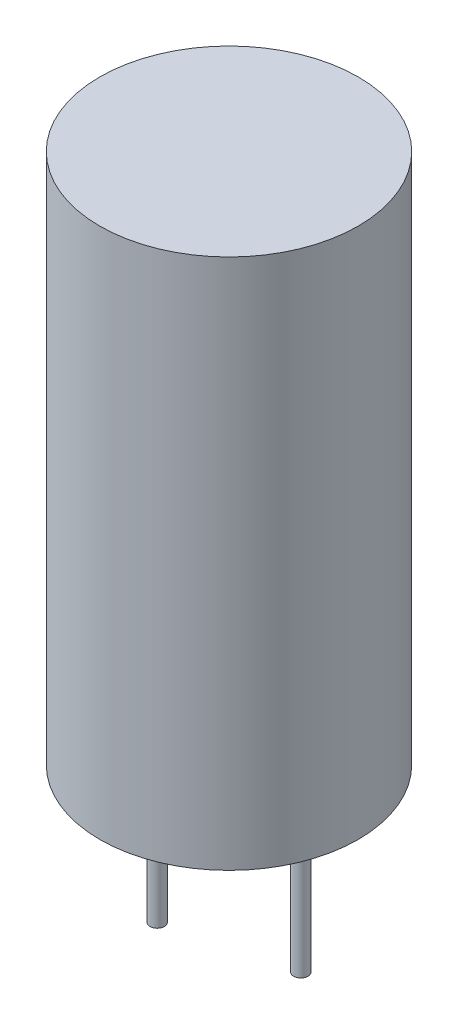
SolidWorks part; units mm, degrees
ref_plane "前视基准面" through (0, 0, 0) normal (0, 0, 1) x (1, 0, 0)
ref_plane "上视基准面" through (0, 0, 0) normal (0, 1, 0) x (1, 0, 0)
ref_plane "右视基准面" through (0, 0, 0) normal (1, 0, 0) x (0, 0, -1)
sketch "草图1" plane through (0, 0, 0) normal (0, 1, 0) x (1, 0, 0)
  circle A0 centre (0, 0) radius 9
  dimension "D1" = 18
extrude "拉伸1" add sketch "草图1" along normal blind 37
sketch "草图2" plane through (0, 0, 0) normal (0, -1, 0) x (1, 0, 0)
  line L0 (4.8023, 0) -> (-11.2367, 0) construction
  circle A0 centre (-5, 0) radius 0.5
  dimension "D2" = 1
  dimension "D1" = 5
extrude "拉伸2" add sketch "草图2" along normal blind 12
sketch "草图3" plane through (0, 0, 0) normal (0, -1, 0) x (1, 0, 0)
  line L0 (7.1249, 0) -> (-2.8562, 0) construction
  circle A0 centre (5, 0) radius 0.5
  dimension "D1" = 1
  dimension "D2" = 5
extrude "拉伸3" add sketch "草图3" along normal blind 10
